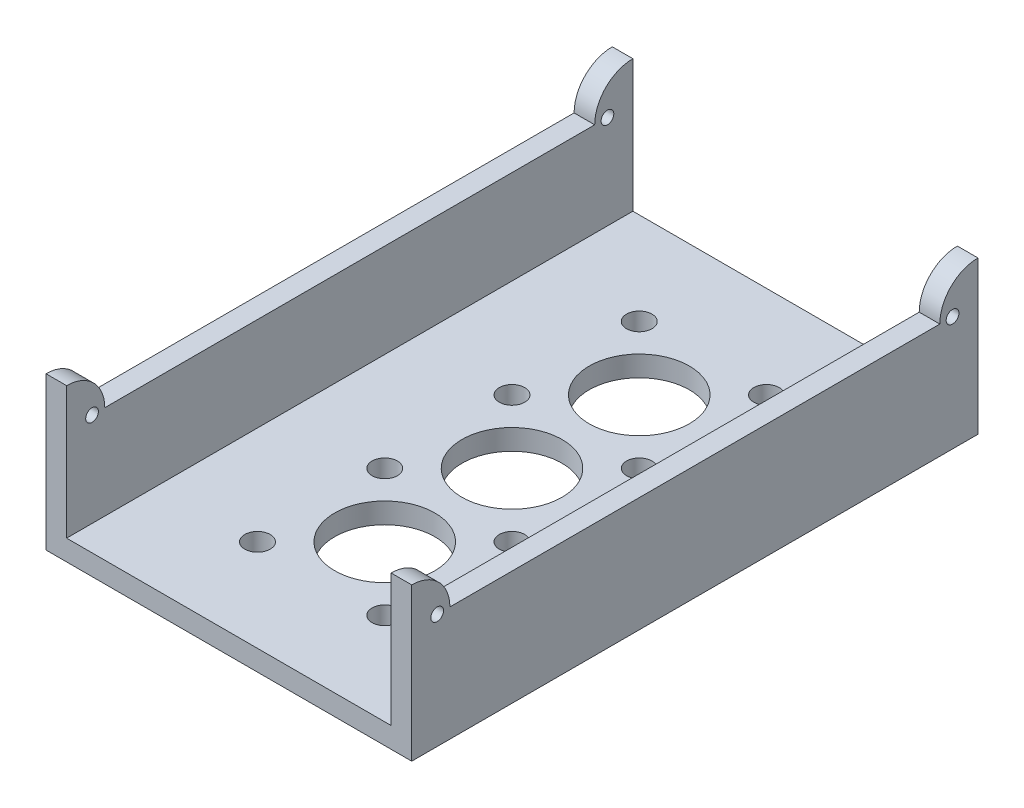
SolidWorks part; units mm, degrees
ref_plane "Front Plane" through (0, 0, 0) normal (0, 0, 1) x (1, 0, 0)
ref_plane "Top Plane" through (0, 0, 0) normal (0, 1, 0) x (1, 0, 0)
ref_plane "Right Plane" through (0, 0, 0) normal (1, 0, 0) x (0, 0, -1)
sketch "Sketch1" plane through (0, 0, 0) normal (0, 0, 1) x (1, 0, 0)
  line L0 (0, 0) -> (-14.37, 0)
  line L1 (-14.37, 0) -> (-14.37, 12)
  line L2 (-14.37, 12) -> (-12.75, 12)
  line L3 (-12.75, 12) -> (-12.75, 1.62)
  line L4 (-12.75, 1.62) -> (0, 1.62)
  line L5 (0, 1.62) -> (0, 0)
  point P7 (-13.56, 12)
  point P8 (-6.375, 1.62)
  dimension "D1" = 14.37
  dimension "D2" = 12
  dimension "D3" = 1.62
  dimension "D4" = 1.62
extrude "Boss-Extrude1" add sketch "Sketch1" along normal blind 44.5
sketch "Sketch2" plane through (-14.37, 0, 0) normal (-1, 0, 0) x (0, 0, 1)
  line L0 (0, 12) -> (0, 0) construction
  line L1 (3, 9) -> (41.5, 9)
  line L2 (0, 9) -> (3, 9) construction
  line L3 (44.5, 12) -> (44.5, 0) construction
  line L4 (44.5, 9) -> (41.5, 9) construction
  line L5 (44.5, 9) -> (44.5, 12) construction
  line L6 (0, 12) -> (0, 14.7448)
  line L7 (0, 14.7448) -> (44.5, 14.7448)
  line L8 (44.5, 14.7448) -> (44.5, 12)
  line L9 (44.5, 0) -> (0, 0) construction
  line L10 (44.5, 12) -> (0, 12) construction
  arc A0 (0, 12) -> (3, 9) centre (0, 9) cw
  arc A1 (41.5, 9) -> (44.5, 12) centre (44.5, 9) cw
  circle A2 centre (2, 9) radius 0.5
  circle A3 centre (42.5, 9) radius 0.5
  point P19 (22.25, 12)
  point P23 (2, 9)
  dimension "D2" = 1
  dimension "D4" = 1
  dimension "D1" = 9
  dimension "D3" = 20.25
  dimension "D5" = 40.5
extrude "Cut-Extrude1" cut sketch "Sketch2" against normal blind 44.5
mirror "Mirror1" about plane through (0, 1.62, 44.5) normal (-1, 0, 0) of "Cut-Extrude1", "Boss-Extrude1"
sketch "Sketch3" plane through (0, 0, 0) normal (0, 1, 0) x (1, 0, 0)
  line L0 (0, 0) -> (0, -12.25) construction
  line L1 (12.75, 0) -> (-12.75, 0) construction
  line L2 (12.75, -44.5) -> (12.75, 0) construction
  line L3 (5, -17.25) -> (-5, -17.25) construction
  line L4 (5, -17.25) -> (5, -7.25) construction
  line L5 (5, -7.25) -> (-5, -7.25) construction
  line L6 (-5, -17.25) -> (-5, -7.25) construction
  line L7 (5, -17.25) -> (-5, -7.25) construction
  line L8 (5, -7.25) -> (-5, -17.25) construction
  circle A0 centre (0, -12.25) radius 3.935
  circle A1 centre (-5, -7.25) radius 1
  circle A2 centre (5, -7.25) radius 1
  circle A3 centre (5, -17.25) radius 1
  circle A4 centre (-5, -17.25) radius 1
  circle A5 centre (0, -22.25) radius 3.935
  circle A6 centre (-5, -27.25) radius 1
  circle A7 centre (5, -27.25) radius 1
  circle A8 centre (0, -32.25) radius 3.935
  circle A9 centre (-5, -37.25) radius 1
  circle A10 centre (5, -37.25) radius 1
  point P13 (12.75, -22.25)
  dimension "D1" = 7.87
  dimension "D3" = 2
  dimension "D4" = 10
  dimension "D2" = 45
  dimension "D5" = 10
  dimension "D6" = 3
extrude "Cut-Extrude2" cut sketch "Sketch3" along normal blind 20.5
